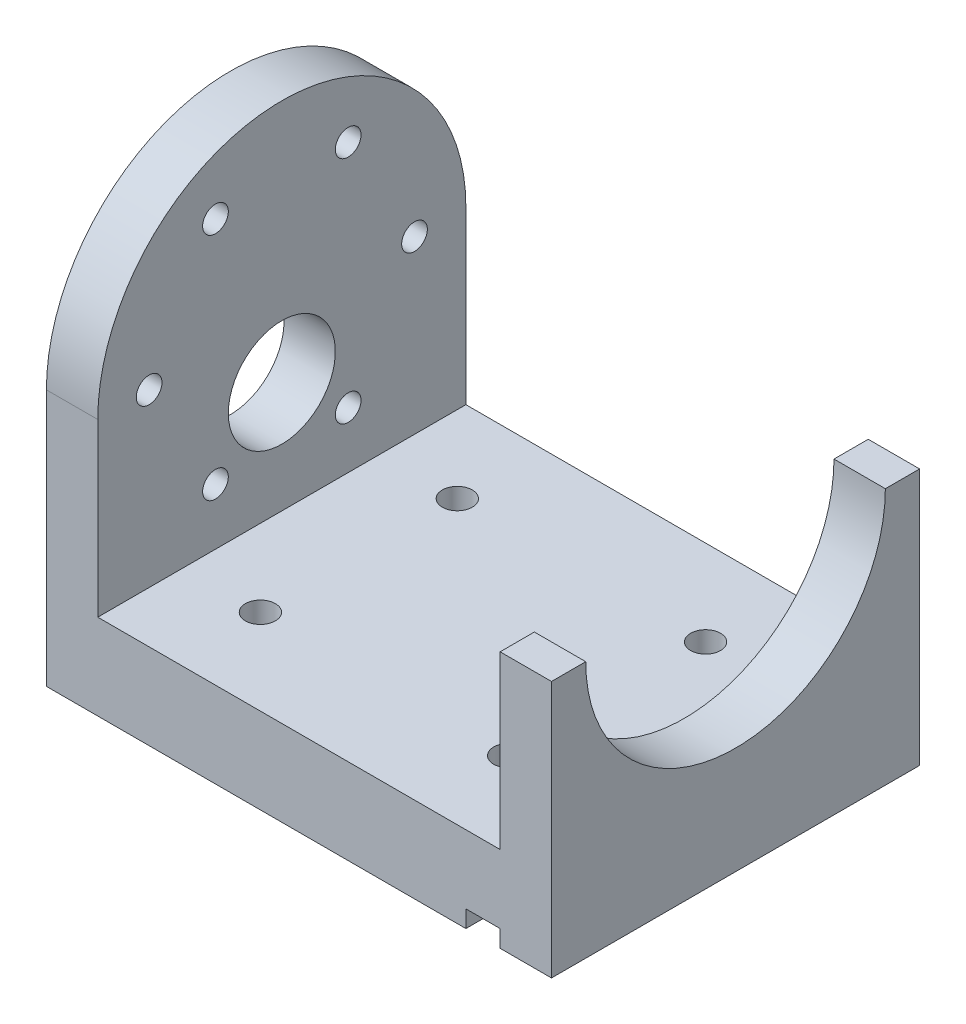
SolidWorks part; units mm, degrees
ref_plane "Front Plane" through (0, 0, 0) normal (0, 0, 1) x (1, 0, 0)
ref_plane "Top Plane" through (0, 0, 0) normal (0, 1, 0) x (1, 0, 0)
ref_plane "Right Plane" through (0, 0, 0) normal (1, 0, 0) x (0, 0, -1)
sketch "Sketch1" plane through (0, 0, 0) normal (0, 1, 0) x (1, 0, 0)
  line L0 (29.5, 43) -> (29.5, 0) construction
  line L1 (0, 0) -> (59, 0)
  line L2 (0, 0) -> (0, 43)
  line L3 (0, 43) -> (59, 43)
  line L4 (59, 0) -> (59, 43)
  line L5 (0, 43) -> (15, 43) construction
  line L6 (0, 43) -> (0, 33) construction
  line L7 (0, 33) -> (15, 33) construction
  line L8 (15, 43) -> (15, 33) construction
  line L9 (0, 21.5) -> (59, 21.5) construction
  circle A0 centre (15, 33) radius 1.75
  circle A1 centre (15, 10) radius 1.75
  circle A2 centre (44, 33) radius 1.75
  circle A3 centre (44, 10) radius 1.75
  dimension "D5" = 3.5
  dimension "D1" = 43
  dimension "D2" = 59
  dimension "D3" = 15
  dimension "D4" = 10
extrude "Boss-Extrude1" add sketch "Sketch1" along normal blind 10
sketch "Sketch2" plane through (0, 0, 0) normal (0, -1, 0) x (1, 0, 0)
  line L0 (0, 0) -> (59, 0) construction
  line L1 (53, 0) -> (49, 0)
  line L2 (53, 0) -> (53, -43)
  line L3 (53, -43) -> (49, -43)
  line L4 (49, 0) -> (49, -43)
  line L5 (59, -43) -> (0, -43) construction
  dimension "D1" = 6
  dimension "D2" = 4
extrude "Cut-Extrude1" cut sketch "Sketch2" against normal blind 2
sketch "Sketch3" plane through (59, 0, 0) normal (1, 0, 0) x (0, 0, -1)
  line L0 (0, 10) -> (43, 10)
  line L1 (0, 10) -> (0, 30)
  line L2 (43, 10) -> (43, 30)
  line L3 (0, 30) -> (4, 30)
  line L4 (39, 30) -> (43, 30)
  line L5 (0, 30) -> (43, 30) construction
  arc A0 (4, 30) -> (39, 30) centre (21.5, 30) ccw
  dimension "D2" = 35
  dimension "D1" = 20
extrude "Boss-Extrude2" add sketch "Sketch3" against normal blind 6 contours A0 L4 L2 L0 L1 L3
sketch "Sketch5" plane through (0, 0, 0) normal (-1, 0, 0) x (0, 0, 1)
  line L0 (-43, 10) -> (0, 10)
  line L1 (-43, 10) -> (-43, 30)
  line L2 (0, 10) -> (0, 30)
  line L4 (-43, 30) -> (0, 30) construction
  line L6 (-21.5, 30) -> (-21.5, 23) construction
  arc A0 (0, 30) -> (-43, 30) centre (-21.5, 30) ccw
  circle A1 centre (-21.5, 23) radius 6.25
  circle A2 centre (-21.5, 30) radius 15.5 construction
  circle A3 centre (-6, 30) radius 1.5
  circle A4 centre (-13.75, 16.5766) radius 1.5
  circle A5 centre (-29.25, 16.5766) radius 1.5
  circle A6 centre (-37, 30) radius 1.5
  circle A7 centre (-29.25, 43.4234) radius 1.5
  circle A8 centre (-13.75, 43.4234) radius 1.5
  point P12 (-6, 30)
  point P27 (-21.5, 30)
  dimension "D2" = 12.5
  dimension "D3" = 31
  dimension "D4" = 3
  dimension "D1" = 7
  dimension "D5" = 6
extrude "Boss-Extrude3" add sketch "Sketch5" against normal blind 6
